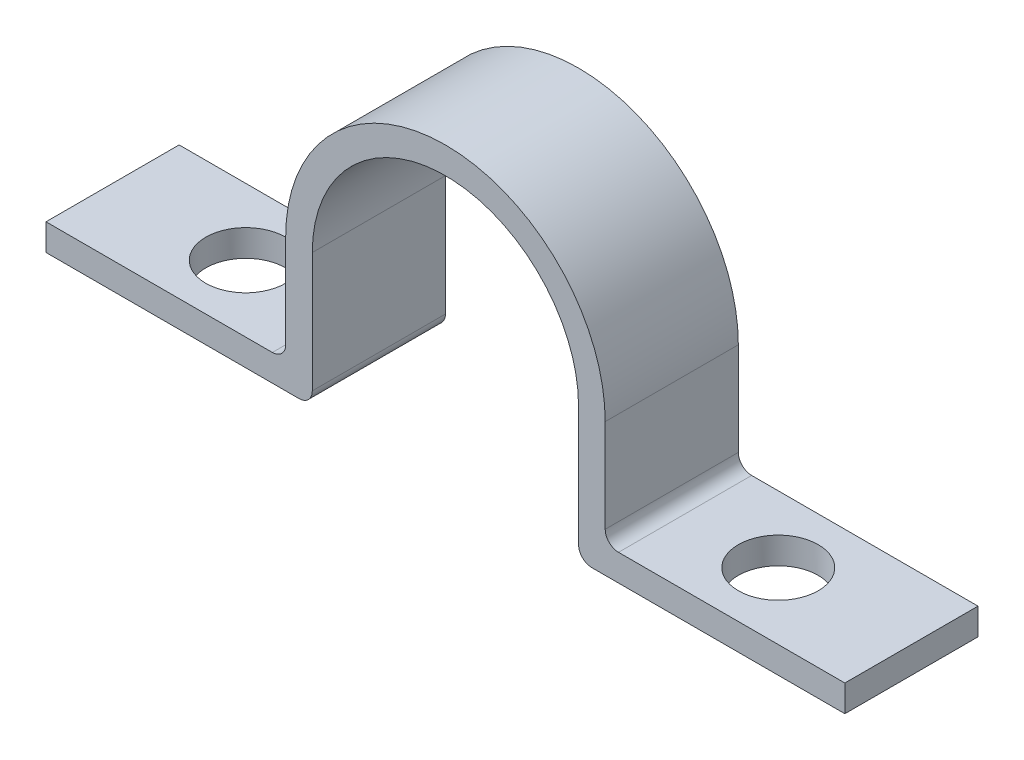
SolidWorks part; units mm, degrees
material "201 退火不锈钢 (SS)"
ref_plane "前视基准面" through (0, 0, 0) normal (0, 0, 1) x (1, 0, 0)
ref_plane "上视基准面" through (0, 0, 0) normal (0, 1, 0) x (1, 0, 0)
ref_plane "右视基准面" through (0, 0, 0) normal (1, 0, 0) x (0, 0, -1)
other "Configuration Table"
sketch "草图1" plane through (0, 0, 0) normal (0, 0, 1) x (1, 0, 0)
  line L0 (-174.7192, 0) -> (8561.2384, 0) construction
  line L1 (-5, 5) -> (-5, 0.5)
  line L2 (-5.5, 0) -> (-15, 0)
  line L3 (0, -995) -> (0, 49005) construction
  line L4 (5.5, 0) -> (15, 0)
  line L5 (5, 5) -> (5, 0.5)
  line L6 (6.5, 1) -> (15, 1)
  line L7 (6, 5) -> (6, 1.5)
  line L8 (-6, 5) -> (-6, 1.5)
  line L9 (-6.5, 1) -> (-15, 1)
  line L10 (-15, 1) -> (-15, 0)
  line L11 (15, 1) -> (15, 0)
  line L12 (-6, 1) -> (-15, 1) construction
  line L13 (-6, 5) -> (-6, 1) construction
  line L14 (6, 1) -> (15, 1) construction
  line L15 (6, 5) -> (6, 1) construction
  arc A0 (5, 5) -> (-5, 5) centre (0, 5) ccw
  arc A1 (5.5, 0) -> (5, 0.5) centre (5.5, 0.5) cw
  arc A2 (-5, 0.5) -> (-5.5, 0) centre (-5.5, 0.5) cw
  arc A4 (6, 5) -> (-6, 5) centre (0, 5) ccw
  arc A5 (6.5, 1) -> (6, 1.5) centre (6.5, 1.5) cw
  arc A6 (-6.5, 1) -> (-6, 1.5) centre (-6.5, 1.5) ccw
  arc A7 (-6, 1) -> (-6, 1) centre (-6, 1) cw construction
  arc A8 (6, 1) -> (6, 1) centre (6, 1) cw construction
  point P14 (5, 0)
  point P17 (-5, 0)
  dimension "D1" = 10
  dimension "D3" = 0.5
  dimension "D5" = 0.5
  dimension "D6" = 0.5
  dimension "D2" = 30
  dimension "D4" = 1
extrude "凸台-拉伸1" add sketch "草图1" along normal blind 5
sketch "草图2" plane through (0, 1, 0) normal (0, 1, 0) x (1, 0, 0)
  line L0 (-1015, -2.5) -> (48985, -2.5) construction
  line L1 (-15, -5) -> (-15, 0) construction
  circle A0 centre (-10, -2.5) radius 1.5
  circle A1 centre (10, -2.5) radius 1.5
  point P5 (-15, -2.5)
  dimension "D1" = 3
  dimension "D3" = 3
  dimension "D2" = 10
  dimension "D4" = 10
extrude "切除-拉伸1" cut sketch "草图2" against normal through all both and the other way through all
